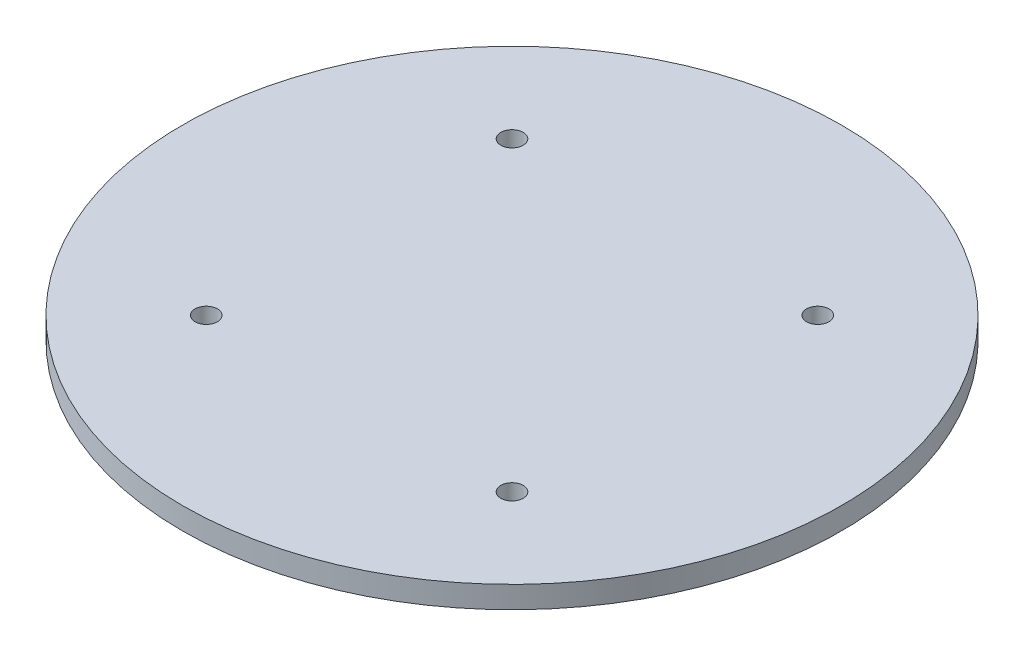
SolidWorks part; units mm, degrees
ref_plane "前视基准面" through (0, 0, 0) normal (0, 0, 1) x (1, 0, 0)
ref_plane "上视基准面" through (0, 0, 0) normal (0, 1, 0) x (1, 0, 0)
ref_plane "右视基准面" through (0, 0, 0) normal (1, 0, 0) x (0, 0, -1)
sketch "草图1" plane through (0, 0, 0) normal (0, 1, 0) x (1, 0, 0)
  circle A0 centre (0, 0) radius 75
  dimension "D1" = 150
extrude "凸台-拉伸1" add sketch "草图1" along normal blind 5
sketch "草图2" plane through (0, 0, 0) normal (0, -1, 0) x (1, 0, 0)
  line L1 (-34.79, -34.79) -> (34.79, -34.79) construction
  line L2 (-34.79, -34.79) -> (-34.79, 34.79) construction
  line L3 (-34.79, 34.79) -> (34.79, 34.79) construction
  line L4 (34.79, -34.79) -> (34.79, 34.79) construction
  line L5 (-34.79, -34.79) -> (34.79, 34.79) construction
  line L6 (-34.79, 34.79) -> (34.79, -34.79) construction
  point P0 (0, 0)
  point P1 (34.79, 34.79)
  point P2 (-34.79, -34.79)
  point P3 (-34.79, 34.79)
  point P4 (34.79, -34.79)
  dimension "D1" = 69.58
hole_wizard "孔2" positions "草图2" profile "草图4" legacy
sketch "草图4" plane through (34.79, 0, -34.79) normal (1, 0, 0) x (0, 0, -1)
  line L0 (0, 0) -> (0, 5)
  line L1 (0, 5) -> (2.55, 5)
  line L2 (2.55, 5) -> (2.55, 0)
  line L3 (2.55, 0) -> (0, 0)
  line L4 (0, 110) -> (0, -10) construction
  dimension "直径" = 5.1
  dimension "深度" = 5
